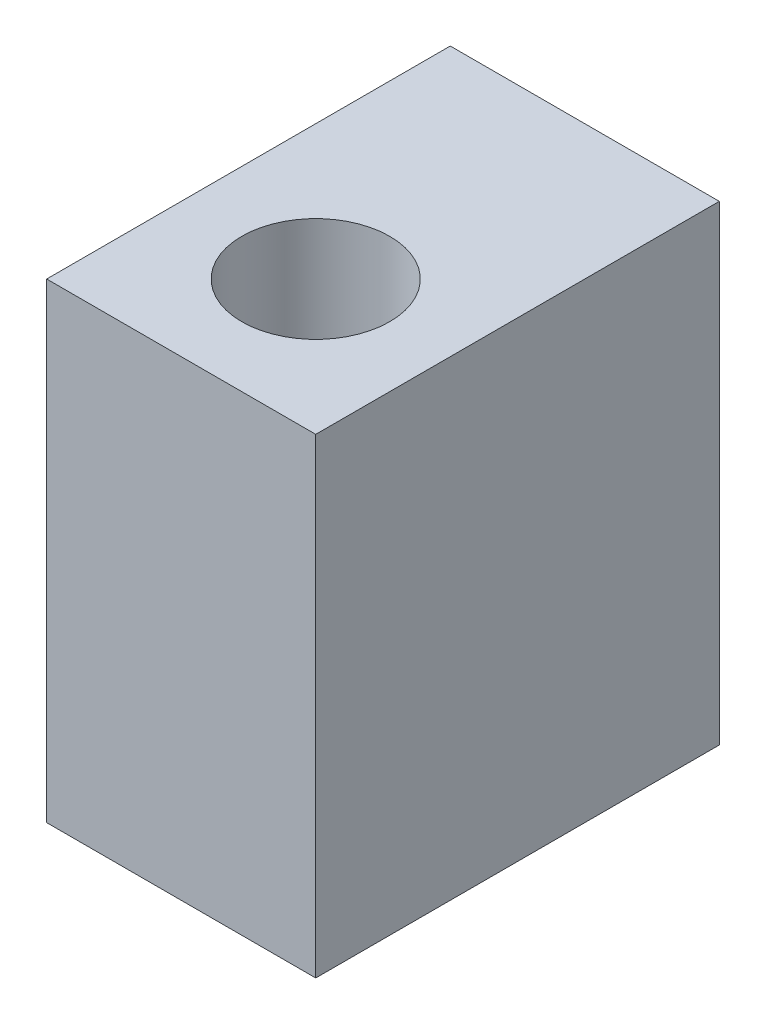
SolidWorks part; units mm, degrees
ref_plane "前视基准面" through (0, 0, 0) normal (0, 0, 1) x (1, 0, 0)
ref_plane "上视基准面" through (0, 0, 0) normal (0, 1, 0) x (1, 0, 0)
ref_plane "右视基准面" through (0, 0, 0) normal (1, 0, 0) x (0, 0, -1)
sketch "草图1" plane through (0, 0, 0) normal (0, 1, 0) x (1, 0, 0)
  line L1 (-1.1875, 0.9922) -> (2.8125, 0.9922)
  line L2 (-1.1875, 0.9922) -> (-1.1875, -5.0078)
  line L3 (-1.1875, -5.0078) -> (2.8125, -5.0078)
  line L4 (2.8125, 0.9922) -> (2.8125, -5.0078)
  line L5 (-1.1875, 0.9922) -> (2.8125, -5.0078) construction
  line L6 (-1.1875, -5.0078) -> (2.8125, 0.9922) construction
  point P4 (0.8125, -2.0078)
  dimension "D1" = 4
  dimension "D2" = 6
extrude "凸台-拉伸1" add sketch "草图1" along normal blind 7
sketch "草图3" plane through (0, 0, 0) normal (0, -1, 0) x (1, 0, 0)
  line L0 (0.8125, 5.0078) -> (0.8125, -0.9922) construction
  line L1 (-1.1875, 5.0078) -> (2.8125, 5.0078) construction
  line L2 (2.8125, -0.9922) -> (-1.1875, -0.9922) construction
  circle A0 centre (0.8125, 3.0078) radius 1.1
  dimension "D1" = 2.2
  dimension "D2" = 2
extrude "切除-拉伸1" cut sketch "草图3" against normal through all
